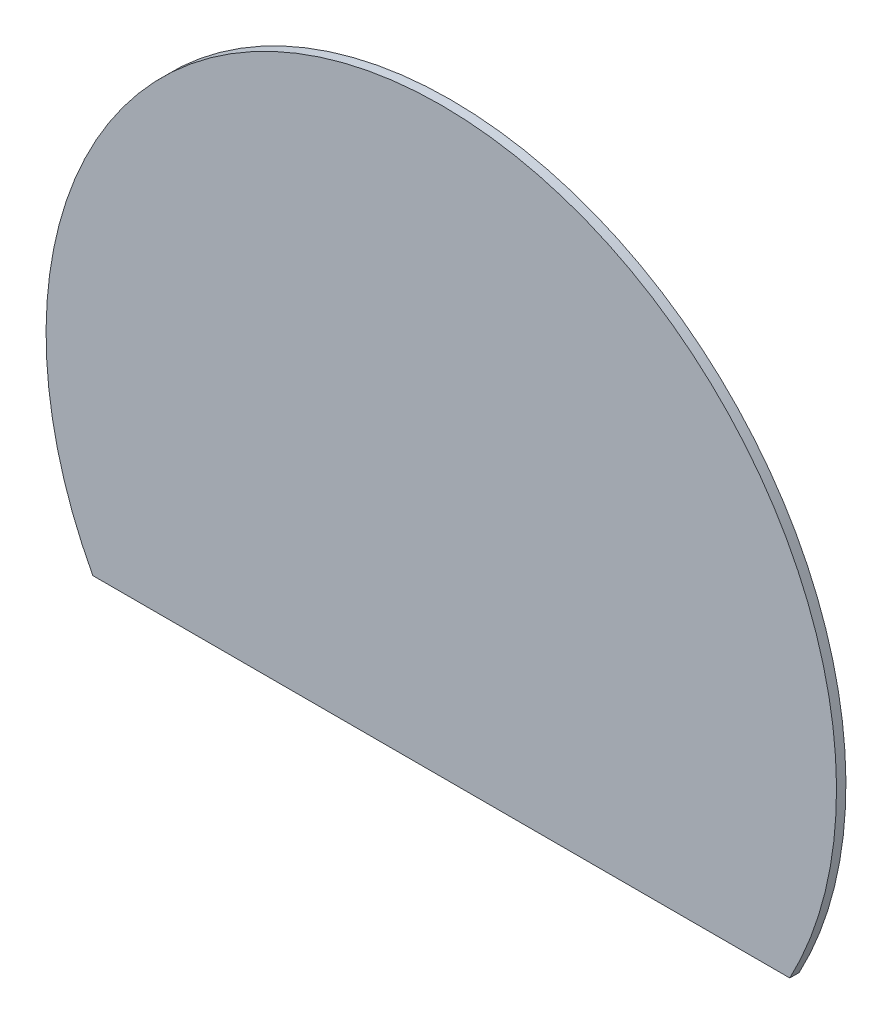
SolidWorks part; units mm, degrees
ref_plane "前视基准面" through (0, 0, 0) normal (0, 0, 1) x (1, 0, 0)
ref_plane "上视基准面" through (0, 0, 0) normal (0, 1, 0) x (1, 0, 0)
ref_plane "右视基准面" through (0, 0, 0) normal (1, 0, 0) x (0, 0, -1)
sketch "草图1" plane through (0, 0, 0) normal (0, 0, 1) x (1, 0, 0)
  line L1 (-13.2256, -99.0769) -> (185.1588, -99.0769)
  line L2 (185.1588, -99.0769) -> (-185.1588, -99.0769)
  arc A0 (185.1588, -99.0769) -> (-185.1588, -99.0769) centre (0, 0) ccw
extrude "凸台-拉伸1" add sketch "草图1" along normal blind 5 contours L1 A0 L2
